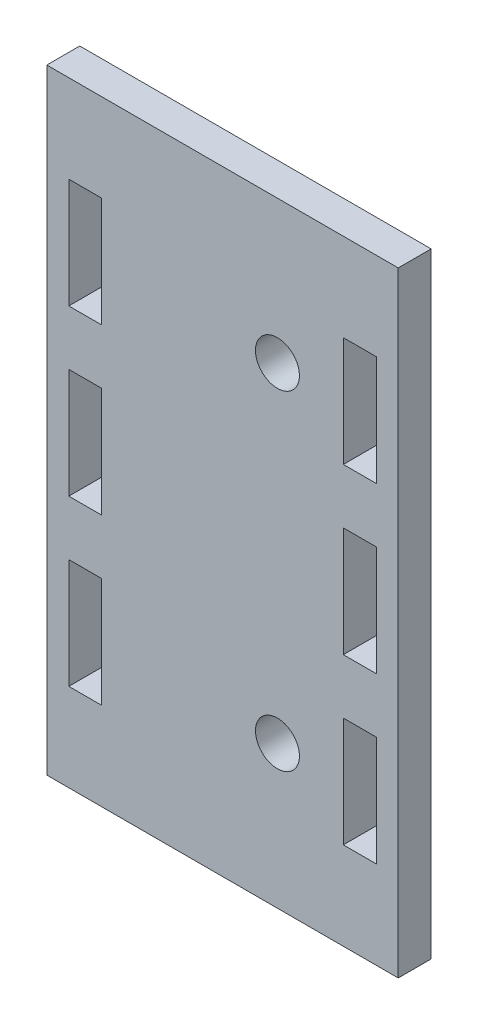
SolidWorks part; units mm, degrees
material "Thornel Mat VMA"
ref_plane "前视基准面" through (0, 0, 0) normal (0, 0, 1) x (1, 0, 0)
ref_plane "上视基准面" through (0, 0, 0) normal (0, 1, 0) x (1, 0, 0)
ref_plane "右视基准面" through (0, 0, 0) normal (1, 0, 0) x (0, 0, -1)
sketch "草图1" plane through (0, 0, 0) normal (0, 0, 1) x (1, 0, 0)
  line L2 (20, 20) -> (20, 10)
  line L8 (20, 5) -> (20, -5)
  line L9 (20, 20) -> (23, 20)
  line L10 (20, 20) -> (20, 10)
  line L11 (20, 10) -> (23, 10)
  line L12 (23, 20) -> (23, 10)
  line L13 (20, 5) -> (23, 5)
  line L14 (23, 5) -> (23, -5)
  line L15 (20, -5) -> (23, -5)
  line L16 (20, -10) -> (20, -20)
  line L17 (20, -10) -> (23, -10)
  line L18 (23, -10) -> (23, -20)
  line L19 (20, -20) -> (23, -20)
  line L21 (25, 25) -> (25, -25)
  line L24 (20, 5) -> (20, -5)
  line L25 (20, -10) -> (20, -20)
  line L26 (-2, -5) -> (-2, 5)
  line L27 (-2, -20) -> (-5, -20)
  line L28 (-2, -20) -> (-2, -10)
  line L29 (-2, -10) -> (-5, -10)
  line L30 (-5, -20) -> (-5, -10)
  line L31 (-2, -5) -> (-5, -5)
  line L32 (-5, -5) -> (-5, 5)
  line L33 (-2, 5) -> (-5, 5)
  line L34 (-2, 10) -> (-2, 20)
  line L35 (-2, 10) -> (-5, 10)
  line L36 (-5, 10) -> (-5, 20)
  line L37 (-2, 20) -> (-5, 20)
  line L38 (-7, 25) -> (-7, -25)
  line L40 (25, 25) -> (25, 28)
  line L41 (25, 28) -> (-7, 28)
  line L42 (-7, 28) -> (-7, 25)
  line L44 (-7, -25) -> (-7, -28)
  line L45 (-7, -28) -> (25, -28)
  line L46 (25, -28) -> (25, -25)
  circle A2 centre (14, -15) radius 2
  circle A3 centre (14, 15) radius 2
  point P0 (-5, 0)
  dimension "D1" = 50
  dimension "D3" = 10
extrude "凸台-拉伸1" add sketch "草图1" along normal blind 3
